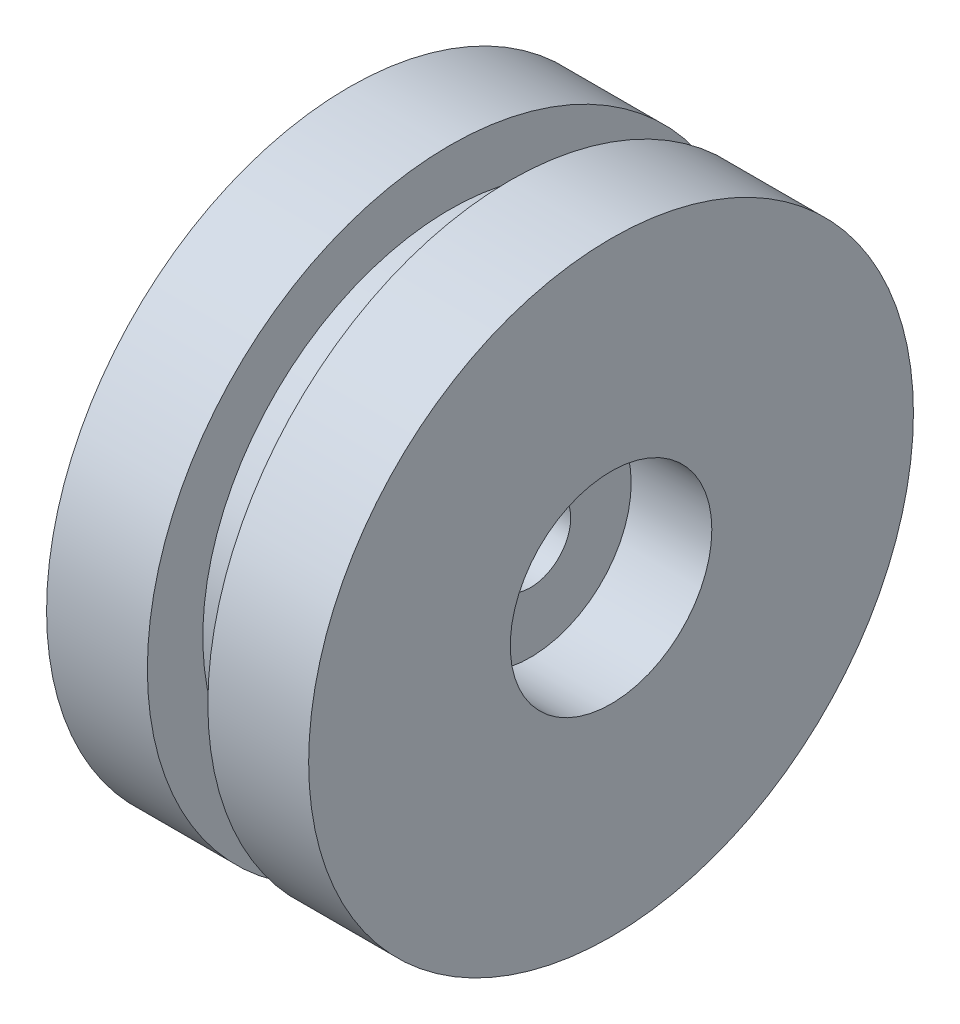
SolidWorks part; units mm, degrees
ref_plane "Front Plane" through (0, 0, 0) normal (0, 0, 1) x (1, 0, 0)
ref_plane "Top Plane" through (0, 0, 0) normal (0, 1, 0) x (1, 0, 0)
ref_plane "Right Plane" through (0, 0, 0) normal (1, 0, 0) x (0, 0, -1)
sketch "Sketch1" plane through (0, 0, 0) normal (0, 0, 1) x (1, 0, 0)
  line L0 (0, -15) -> (0, 15) construction
  line L1 (-1.5, 15) -> (-1.5, 12.25)
  line L2 (-1.5, 12.25) -> (1.5, 12.25)
  line L3 (-1.5, 15) -> (-6.5, 15)
  line L4 (-6.5, 15) -> (-6.5, 0)
  line L5 (-6.5, 0) -> (6.5, 0) construction
  line L6 (6.5, 15) -> (6.5, 0)
  line L7 (1.5, 15) -> (6.5, 15)
  line L8 (1.5, 15) -> (1.5, 12.25)
  line L9 (6.5, 0) -> (-6.5, 0)
  point P4 (0, 0)
  point P12 (0, 0)
  point P15 (0, 12.25)
  dimension "D1" = 30
  dimension "D2" = 24.5
  dimension "D3" = 3
  dimension "D4" = 5
  dimension "D5" = 6.5
revolve "Revolve1" add sketch "Sketch1" angle 360 about L9
sketch "Sketch2" plane through (6.5, 0, 0) normal (1, 0, 0) x (0, 0, -1)
  circle A0 centre (0, 0) radius 5
  dimension "D1" = 10
extrude "Cut-Extrude1" cut sketch "Sketch2" against normal blind 4
sketch "Sketch3" plane through (2.5, 0, 0) normal (1, 0, 0) x (0, 0, -1)
  circle A0 centre (0, 0) radius 2
  dimension "D1" = 4
extrude "Cut-Extrude2" cut sketch "Sketch3" against normal blind 6.5 from surface at 4 starting at face at (6.5, 0, -5)
sketch "Sketch4" plane through (2.5, 0, 0) normal (1, 0, 0) x (0, 0, -1)
  circle A0 centre (0, 0) radius 2.5
  dimension "D1" = 5
extrude "Cut-Extrude4" cut sketch "Sketch4" along normal blind 6.5 from surface at -9 starting at face at (-6.5, 0, -15)
